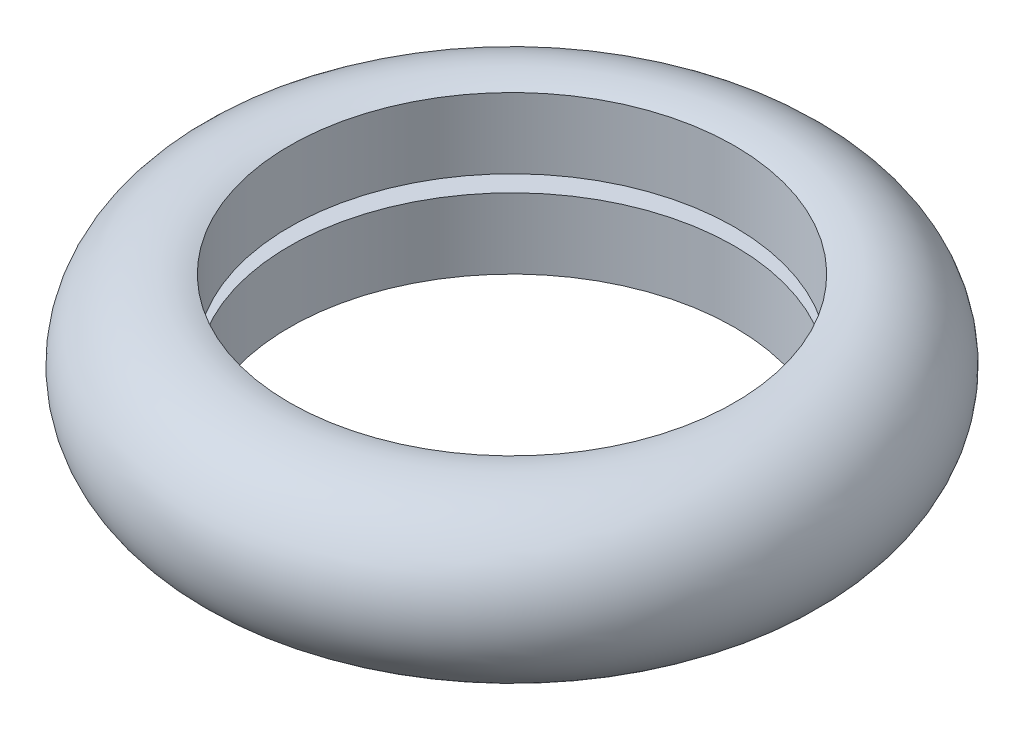
SolidWorks part; units mm, degrees
ref_plane "Front Plane" through (0, 0, 0) normal (0, 0, 1) x (1, 0, 0)
ref_plane "Top Plane" through (0, 0, 0) normal (0, 1, 0) x (1, 0, 0)
ref_plane "Right Plane" through (0, 0, 0) normal (1, 0, 0) x (0, 0, -1)
sketch "Sketch1" plane through (0, 0, 0) normal (0, 0, 1) x (1, 0, 0)
  line L0 (0, 0) -> (0, -11.8663) construction
  line L1 (0, 0) -> (-45, 0) construction
  line L2 (-45, 15) -> (-11, 15)
  line L3 (-45, 15) -> (-45, -15)
  line L4 (-45, -15) -> (-11, -15)
  line L5 (-11, 15) -> (-11, -15)
  line L6 (-45, 15) -> (-37.5, 15)
  line L7 (-45, 15) -> (-45, -15)
  line L8 (-45, -15) -> (-37.5, -15)
  line L9 (-37.5, 15) -> (-37.5, -15)
  line L10 (-11, 15) -> (-16, 15)
  line L11 (-11, 15) -> (-11, -15)
  line L12 (-11, -15) -> (-16, -15)
  line L13 (-16, 15) -> (-16, -15)
  line L15 (-37.5, 15) -> (-40.5, 15)
  line L16 (-37.5, 15) -> (-37.5, -15)
  line L17 (-37.5, -15) -> (-40.5, -15)
  line L18 (-40.5, 15) -> (-40.5, -15)
  line L19 (-40.5, 1.5) -> (-46.5, 1.5)
  line L20 (-40.5, 1.5) -> (-40.5, -1.5)
  line L21 (-40.5, -1.5) -> (-46.5, -1.5)
  line L22 (-46.5, 1.5) -> (-46.5, -1.5)
  circle A0 centre (-45, 0) radius 15
  arc A1 (-37.5, 10) -> (-16, 15) centre (-37.5, 58.725) ccw
  arc A2 (-37.5, -10) -> (-16, -15) centre (-37.5, -58.725) cw
  point P24 (-46.5, 0)
  dimension "D1" = 60
  dimension "D2" = 30
  dimension "D3" = 11
  dimension "D4" = 5
  dimension "D5" = 5
  dimension "D6" = 7.5
  dimension "D7" = 3
  dimension "D8" = 6
  dimension "D9" = 3
revolve "Revolve1" add sketch "Sketch1" angle 360 about L0
